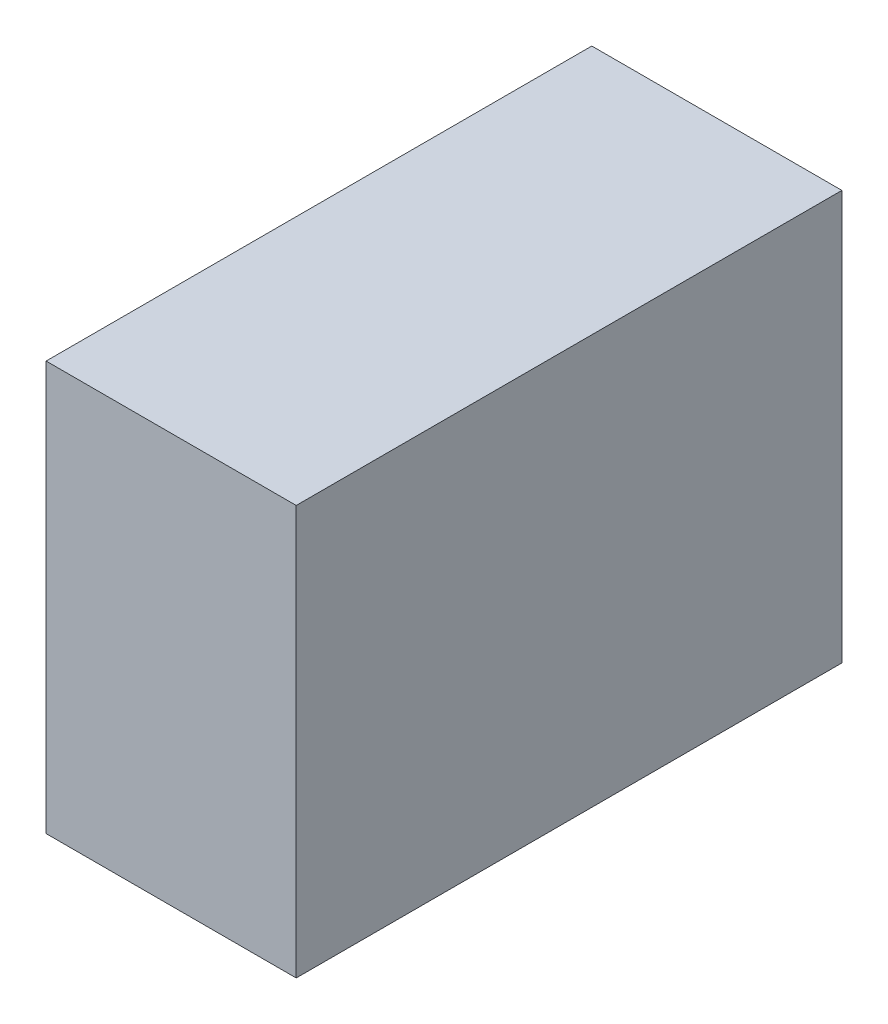
SolidWorks part; units mm, degrees
ref_plane "Front" through (0, 0, 0) normal (0, 0, 1) x (1, 0, 0)
ref_plane "Top" through (0, 0, 0) normal (0, 1, 0) x (1, 0, 0)
ref_plane "Right" through (0, 0, 0) normal (1, 0, 0) x (0, 0, -1)
sketch "Sketch1" plane through (0, 0, 0) normal (0, 0, 1) x (1, 0, 0)
  line L1 (32.2462, 93.726) -> (26.7462, 93.726)
  line L2 (32.2462, 93.726) -> (32.2462, 84.726)
  line L3 (32.2462, 84.726) -> (26.7462, 84.726)
  line L4 (26.7462, 93.726) -> (26.7462, 84.726)
  dimension "D1" = 9
  dimension "D2" = 5.5
extrude "Boss-Extrude1" add sketch "Sketch1" along normal blind 12
